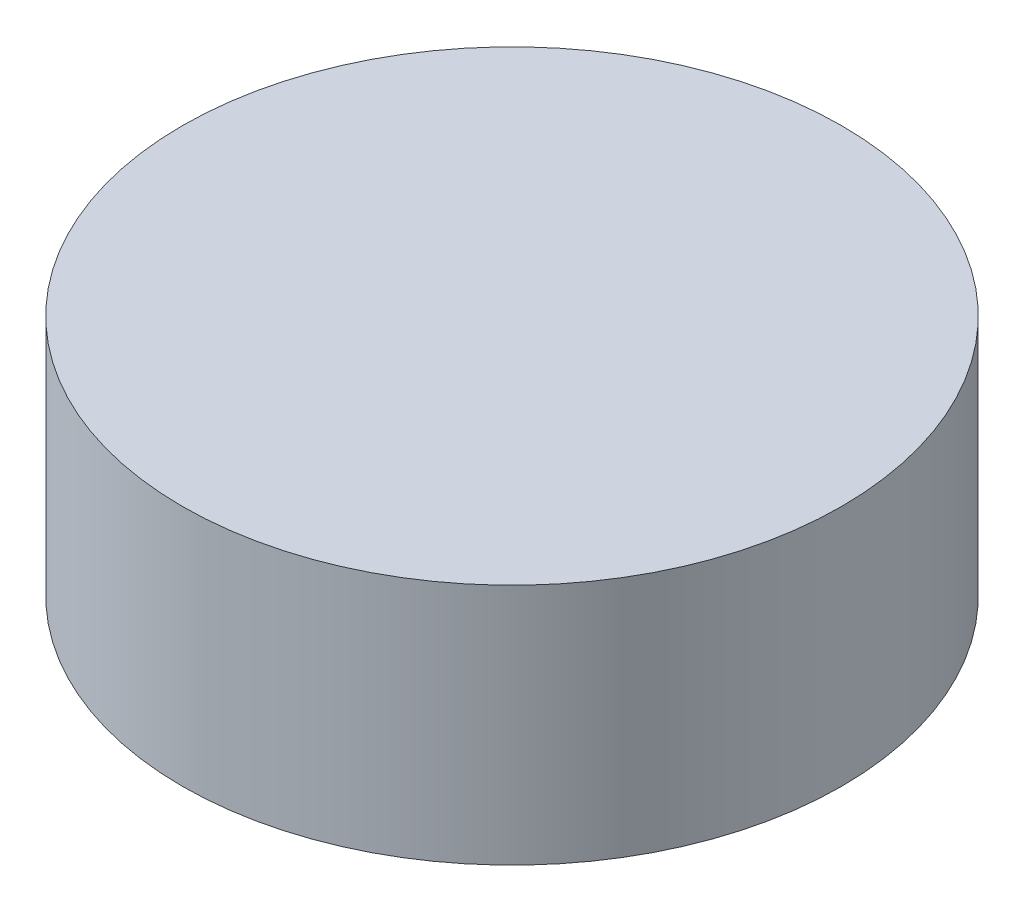
SolidWorks part; units mm, degrees
ref_plane "前视基准面" through (0, 0, 0) normal (0, 0, 1) x (1, 0, 0)
ref_plane "上视基准面" through (0, 0, 0) normal (0, 1, 0) x (1, 0, 0)
ref_plane "右视基准面" through (0, 0, 0) normal (1, 0, 0) x (0, 0, -1)
other "Configuration Table"
sketch "草图1" plane through (0, 0, 0) normal (0, 1, 0) x (1, 0, 0)
  circle A0 centre (0, 0) radius 13.6
extrude "凸台-拉伸1" add sketch "草图1" along normal blind 10
